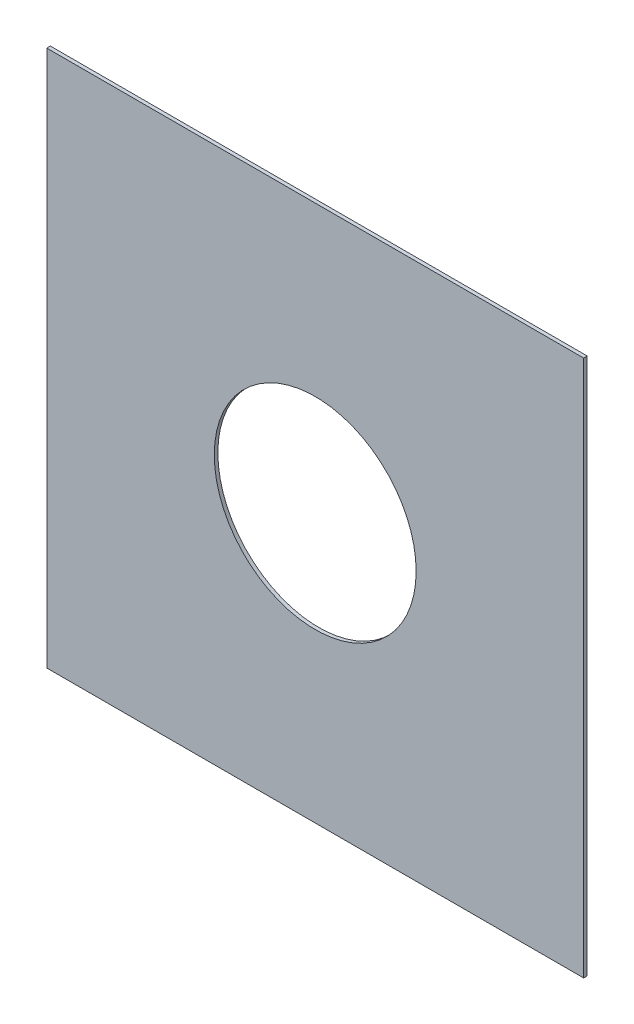
SolidWorks part; units mm, degrees
ref_plane "Front Plane" through (0, 0, 0) normal (0, 0, 1) x (1, 0, 0)
ref_plane "Top Plane" through (0, 0, 0) normal (0, 1, 0) x (1, 0, 0)
ref_plane "Right Plane" through (0, 0, 0) normal (1, 0, 0) x (0, 0, -1)
sketch "Sketch1" plane through (0, 0, 0) normal (0, 0, 1) x (1, 0, 0)
  line L1 (-19.05, 19.05) -> (19.05, 19.05)
  line L2 (-19.05, 19.05) -> (-19.05, -19.05)
  line L3 (-19.05, -19.05) -> (19.05, -19.05)
  line L4 (19.05, 19.05) -> (19.05, -19.05)
  point P4 (19.05, 0)
  point P5 (0, 19.05)
  dimension "D1" = 38.1
extrude "Boss-Extrude1" add sketch "Sketch1" along normal blind 0.254
sketch "Sketch3" plane through (0, 0, 0) normal (0, 0, 1) x (1, 0, 0)
  circle A0 centre (0, 0) radius 7.1628
  dimension "D1" = 14.3256
extrude "Cut-Extrude2" cut sketch "Sketch3" along normal through all
sketch "Sketch2" plane through (0, 0, 0) normal (0, 0, 1) x (1, 0, 0)
  circle A0 centre (10.16, 10.16) radius 0.762
  circle A1 centre (-10.16, 10.16) radius 0.762
  circle A2 centre (-10.16, -10.16) radius 0.762
  circle A3 centre (10.16, -10.16) radius 0.762
  dimension "D1" = 1.524
extrude "Cut-Extrude1" [suppressed] cut sketch "Sketch2" along normal through all
